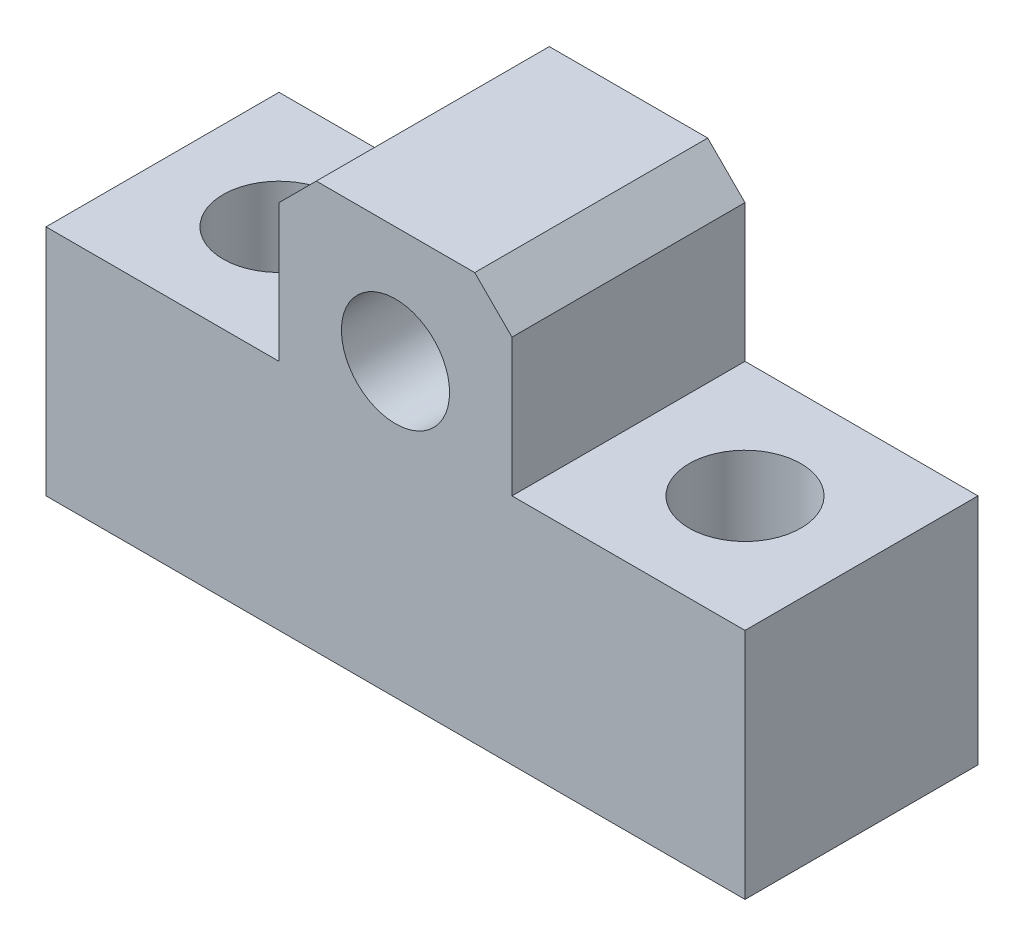
SolidWorks part; units mm, degrees
material "6061-T6 (SS)"
ref_plane "Front Plane" through (0, 0, 0) normal (0, 0, 1) x (1, 0, 0)
ref_plane "Top Plane" through (0, 0, 0) normal (0, 1, 0) x (1, 0, 0)
ref_plane "Right Plane" through (0, 0, 0) normal (1, 0, 0) x (0, 0, -1)
sketch "Sketch1" plane through (0, 0, 0) normal (0, 0, 1) x (1, 0, 0)
  line L0 (-9.525, 3.175) -> (9.525, -3.175) construction
  line L1 (-9.525, 3.175) -> (9.525, 3.175)
  line L2 (-9.525, 3.175) -> (-9.525, -3.175)
  line L3 (-9.525, -3.175) -> (9.525, -3.175)
  line L4 (9.525, 3.175) -> (9.525, -3.175)
  point P4 (0, 0)
  dimension "D1" = 19.05
  dimension "D2" = 6.35
extrude "Boss-Extrude1" add sketch "Sketch1" along normal blind 6.35
sketch "Sketch6" plane through (0, 3.175, 0) normal (0, 1, 0) x (1, 0, 0)
  line L0 (9.525, 0) -> (-9.525, 0) construction
  line L1 (3.175, 0) -> (-3.175, 0)
  line L2 (3.175, 0) -> (3.175, -6.35)
  line L3 (3.175, -6.35) -> (-3.175, -6.35)
  line L4 (-3.175, 0) -> (-3.175, -6.35)
  line L5 (9.525, -6.35) -> (-9.525, -6.35) construction
  point P8 (0, 0)
  point P9 (0, 0)
  dimension "D1" = 6.35
extrude "Boss-Extrude2" add sketch "Sketch6" along normal blind 4.7625
hole_wizard "Tapped Hole for #4-40 Helicoil1" positions "Sketch2" profile "Sketch3" tap size "#4-40" standard "Helicoil® Inch" end condition through all
sketch "Sketch2" plane through (0, 3.175, 0) normal (0, 1, 0) x (1, 0, 0)
  line L0 (0, 0) -> (0, -6.35) construction
  line L4 (-9.525, -6.35) -> (-9.525, 0) construction
  line L5 (-9.525, -6.35) -> (9.525, -6.35) construction
  line L6 (-9.525, 0) -> (9.525, 0) construction
  point P0 (-6.35, -3.175)
  point P13 (6.35, -3.175)
  point P16 (0, -3.175)
  dimension "D1" = 3.175
sketch "Sketch3" plane through (-6.35, 3.175, 3.175) normal (1, 0, 0) x (0, 0, 1)
  line L0 (0, 0) -> (0, 6.35)
  line L1 (0, 6.35) -> (1.524, 6.35)
  line L2 (1.524, 6.35) -> (1.524, 0)
  line L5 (1.524, 0) -> (0, 0)
  line L11 (0, -6.35) -> (0, 107.95) construction
  dimension "Thru Tap Drill Dia." = 3.048
  dimension "Thru Tap Drill Depth" = 6.35
cosmetic thread "Hole Thread1" parameters "D1"=3.556, "D2"=3.7414
cosmetic thread "Hole Thread2" parameters "D1"=3.556, "D2"=3.7414
hole_wizard "#4 Clearance Hole1" positions "Sketch4" profile "Sketch5" hole size "#4" standard "ANSI Inch" end condition through all
sketch "Sketch4" plane through (0, 0, 6.35) normal (0, 0, 1) x (1, 0, 0)
  line L6 (-3.175, 4.7625) -> (0, 4.7625) construction
  line L7 (-3.175, 7.9375) -> (-3.175, 3.175) construction
  line L8 (0, 4.7625) -> (0, 7.9375) construction
  line L9 (-3.175, 7.9375) -> (3.175, 7.9375) construction
  point P0 (0, 4.7625)
sketch "Sketch5" plane through (0, 4.7625, 6.35) normal (1, 0, 0) x (0, -1, 0)
  line L0 (0, 0) -> (0, 6.35)
  line L1 (0, 6.35) -> (1.4732, 6.35)
  line L2 (1.4732, 6.35) -> (1.4732, 0)
  line L5 (1.4732, 0) -> (0, 0)
  line L11 (0, -6.35) -> (0, 107.95) construction
  dimension "Thru Hole Dia." = 2.9464
  dimension "Thru Hole Depth" = 6.35
chamfer "distinguishingMark" distance 1.016 angle 45 2 edges at (3.175, 7.9375, 3.175) (-3.175, 7.9375, 3.175)
